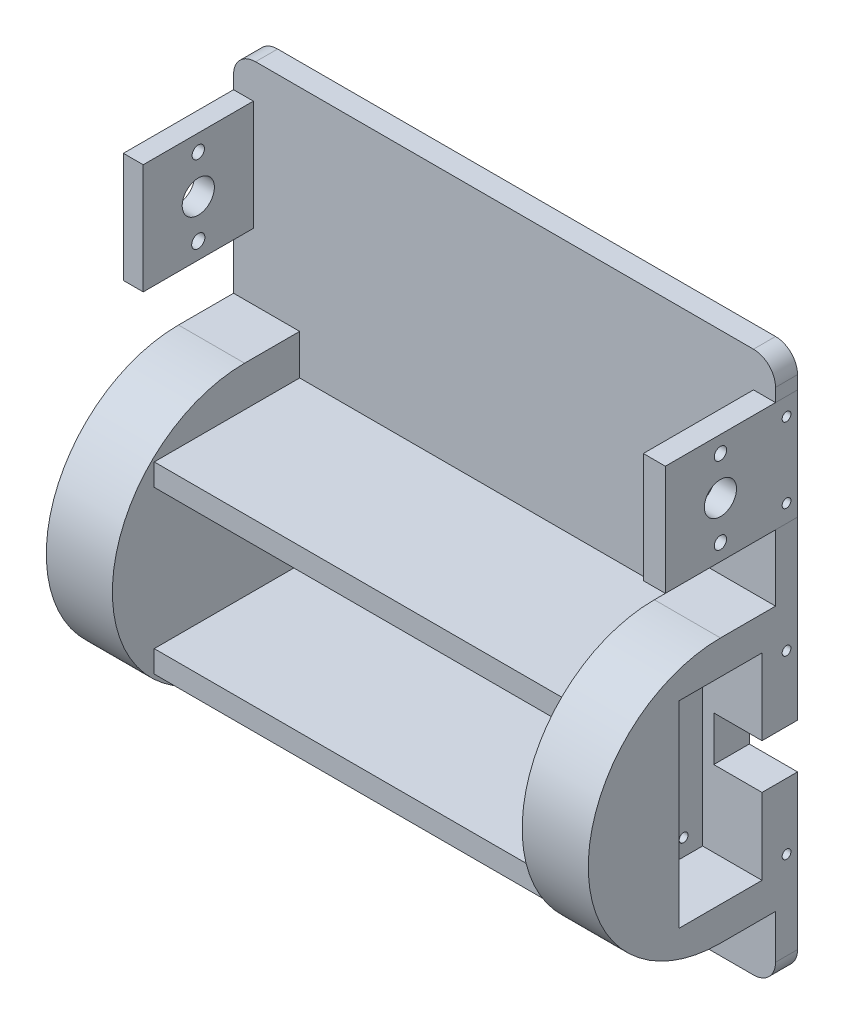
SolidWorks part; units mm, degrees
ref_plane "Plano frontal" through (0, 0, 0) normal (0, 0, 1) x (1, 0, 0)
ref_plane "Plano superior" through (0, 0, 0) normal (0, 1, 0) x (1, 0, 0)
ref_plane "Plano direito" through (0, 0, 0) normal (1, 0, 0) x (0, 0, -1)
sketch "Esboço1" plane through (0, 0, 0) normal (0, 0, 1) x (1, 0, 0)
  line L1 (-47.8109, 58.4855) -> (65.1891, 58.4855)
  line L2 (-52.8109, 53.4855) -> (-52.8109, -59.5145)
  line L3 (-47.8109, -64.5145) -> (65.1891, -64.5145)
  line L4 (70.1891, 53.4855) -> (70.1891, -59.5145)
  arc A0 (70.1891, 53.4855) -> (65.1891, 58.4855) centre (65.1891, 53.4855) ccw
  arc A1 (70.1891, -59.5145) -> (65.1891, -64.5145) centre (65.1891, -59.5145) cw
  arc A2 (-52.8109, -59.5145) -> (-47.8109, -64.5145) centre (-47.8109, -59.5145) ccw
  arc A3 (-52.8109, 53.4855) -> (-47.8109, 58.4855) centre (-47.8109, 53.4855) cw
  dimension "D1" = 5
extrude "Ressalto-extrusão1" add sketch "Esboço1" along normal blind 5
sketch "Esboço4" plane through (0, 0, 5) normal (0, 0, 1) x (1, 0, 0)
  line L0 (-52.8109, 53.4855) -> (-52.8109, -59.5145) construction
  line L1 (-52.8109, 50.4855) -> (-48.3154, 50.4855)
  line L2 (-52.8109, 50.4855) -> (-52.8109, 25.4855)
  line L3 (-52.8109, 25.4855) -> (-48.3154, 25.4855)
  line L4 (-48.3154, 50.4855) -> (-48.3154, 25.4855)
  line L5 (65.1891, 58.4855) -> (-47.8109, 58.4855) construction
  dimension "D1" = 8
extrude "Corte-extrusão2" cut sketch "Esboço4" against normal blind 5
sketch "Esboço5" plane through (0, 0, 5) normal (0, 0, 1) x (1, 0, 0)
  line L1 (-52.8109, 50.4855) -> (-48.3154, 50.4855)
  line L2 (-52.8109, 50.4855) -> (-52.8109, 25.4855)
  line L3 (-52.8109, 25.4855) -> (-48.3154, 25.4855)
  line L4 (-48.3154, 50.4855) -> (-48.3154, 25.4855)
extrude "Ressalto-extrusão2" add sketch "Esboço5" along normal blind 25 and the other way blind 5 separate body
sketch "Esboço6" plane through (-52.8109, 0, 0) normal (-1, 0, 0) x (0, 0, 1)
  line L0 (0, 50.4855) -> (5, 50.4855) construction
  line L1 (0, 50.4855) -> (0, 25.4855) construction
  circle A0 centre (2.5, 46.4855) radius 1
  point P4 (2.5, 50.4855)
  dimension "D1" = 4
  dimension "D2" = 2.5
extrude "Corte-extrusão3" cut sketch "Esboço6" against normal blind 10
sketch "Esboço7" plane through (-52.8109, 0, 0) normal (-1, 0, 0) x (0, 0, 1)
  line L0 (0, 25.4855) -> (5, 25.4855) construction
  line L1 (0, 50.4855) -> (0, 25.4855) construction
  circle A0 centre (2.5, 29.4855) radius 1
  point P4 (2.5, 25.4855)
  dimension "D1" = 4
  dimension "D2" = 2.5
extrude "Corte-extrusão4" cut sketch "Esboço7" against normal blind 10
sketch "Esboço8" plane through (-48.3154, 0, 0) normal (1, 0, 0) x (0, 0, -1)
  line L0 (0, 50.4855) -> (-30, 50.4855) construction
  line L1 (-30, 25.4855) -> (-30, 50.4855) construction
  circle A0 centre (-17.5, 37.9855) radius 3.65
  dimension "D1" = 12.5
  dimension "D2" = 12.5
extrude "Corte-extrusão5" cut sketch "Esboço8" against normal blind 10
sketch "Esboço9" plane through (-52.8109, 0, 0) normal (-1, 0, 0) x (0, 0, 1)
  line L1 (30, 50.4855) -> (30, 25.4855) construction
  circle A0 centre (17.5, 46.7355) radius 1.4
  circle A1 centre (17.5, 37.9855) radius 3.65 construction
  dimension "D1" = 8.75
  dimension "D2" = 12.5
extrude "Corte-extrusão6" cut sketch "Esboço9" against normal blind 10
sketch "Esboço10" plane through (-52.8109, 0, 0) normal (-1, 0, 0) x (0, 0, 1)
  line L0 (30, 50.4855) -> (30, 25.4855) construction
  circle A0 centre (17.5, 29.2355) radius 1.5
  circle A1 centre (17.5, 37.9855) radius 3.65 construction
  dimension "D1" = 8.75
  dimension "D2" = 12.5
extrude "Corte-extrusão7" cut sketch "Esboço10" against normal blind 10
sketch "Esboço11" plane through (0, 0, 5) normal (0, 0, 1) x (1, 0, 0)
  line L0 (70.1891, -59.5145) -> (70.1891, 53.4855) construction
  line L1 (70.1891, 50.4855) -> (65.1891, 50.4855)
  line L2 (70.1891, 50.4855) -> (70.1891, 25.4855)
  line L3 (70.1891, 25.4855) -> (65.1891, 25.4855)
  line L4 (65.1891, 50.4855) -> (65.1891, 25.4855)
  line L5 (65.1891, 58.4855) -> (-47.8109, 58.4855) construction
  dimension "D1" = 8
extrude "Corte-extrusão8" cut sketch "Esboço11" against normal blind 10
sketch "Esboço16" plane through (0, 0, 5) normal (0, 0, 1) x (1, 0, 0)
  line L1 (65.1891, 50.4855) -> (70.1891, 50.4855)
  line L2 (65.1891, 50.4855) -> (65.1891, 25.4855)
  line L3 (65.1891, 25.4855) -> (70.1891, 25.4855)
  line L4 (70.1891, 50.4855) -> (70.1891, 25.4855)
extrude "Ressalto-extrusão3" add sketch "Esboço16" along normal blind 25 and the other way blind 5 separate body
sketch "Esboço17" plane through (70.1891, 0, 0) normal (1, 0, 0) x (0, 0, -1)
  line L0 (0, 50.4855) -> (-5, 50.4855) construction
  line L1 (0, 25.4855) -> (0, 50.4855) construction
  circle A0 centre (-2.5, 46.4855) radius 1
  dimension "D1" = 4
  dimension "D2" = 2.5
extrude "Corte-extrusão9" cut sketch "Esboço17" against normal blind 10
sketch "Esboço18" plane through (70.1891, 0, 0) normal (1, 0, 0) x (0, 0, -1)
  line L0 (0, 25.4855) -> (-30, 25.4855) construction
  line L1 (0, 25.4855) -> (0, 50.4855) construction
  circle A0 centre (-2.5, 29.4855) radius 1
  dimension "D1" = 4
  dimension "D2" = 2.5
extrude "Corte-extrusão10" cut sketch "Esboço18" against normal blind 10
sketch "Esboço20" plane through (70.1891, 0, 0) normal (1, 0, 0) x (0, 0, -1)
  line L0 (-30, 25.4855) -> (-30, 50.4855) construction
  line L1 (0, 50.4855) -> (-30, 50.4855) construction
  circle A0 centre (-17.5, 37.9855) radius 3.65
  dimension "D1" = 12.5
  dimension "D2" = 12.5
extrude "Corte-extrusão11" cut sketch "Esboço20" against normal blind 6
sketch "Esboço22" plane through (70.1891, 0, 0) normal (1, 0, 0) x (0, 0, -1)
  line L1 (-30, 25.4855) -> (-30, 50.4855) construction
  circle A0 centre (-17.5, 46.7355) radius 1.4
  circle A1 centre (-17.5, 37.9855) radius 3.65 construction
  dimension "D1" = 8.75
  dimension "D2" = 12.5
extrude "Corte-extrusão12" cut sketch "Esboço22" against normal blind 5
sketch "Esboço23" plane through (70.1891, 0, 0) normal (1, 0, 0) x (0, 0, -1)
  line L0 (-30, 25.4855) -> (-30, 50.4855) construction
  circle A0 centre (-17.5, 29.2355) radius 1.4
  circle A1 centre (-17.5, 37.9855) radius 3.65 construction
  dimension "D1" = 12.5
  dimension "D2" = 8.75
extrude "Corte-extrusão13" cut sketch "Esboço23" against normal blind 5
sketch "Esboço24" plane through (0, 0, 5) normal (0, 0, 1) x (1, 0, 0)
  line L0 (-52.8109, 25.4855) -> (-52.8109, -59.5145) construction
  line L1 (-52.8109, -49.5145) -> (-37.8109, -49.5145)
  line L2 (-52.8109, -49.5145) -> (-52.8109, 10.4855)
  line L3 (-52.8109, 10.4855) -> (-37.8109, 10.4855)
  line L4 (-37.8109, -49.5145) -> (-37.8109, 10.4855)
  line L6 (-47.8109, -64.5145) -> (65.1891, -64.5145) construction
  dimension "D1" = 15
extrude "Corte-extrusão14" cut sketch "Esboço24" against normal blind 10
sketch "Esboço27" plane through (0, 0, 5) normal (0, 0, 1) x (1, 0, 0)
  line L0 (70.1891, -59.5145) -> (70.1891, 25.4855) construction
  line L1 (70.1891, -49.5145) -> (55.1891, -49.5145)
  line L2 (70.1891, -49.5145) -> (70.1891, 10.4855)
  line L3 (70.1891, 10.4855) -> (55.1891, 10.4855)
  line L4 (55.1891, -49.5145) -> (55.1891, 10.4855)
  line L5 (-52.8109, -49.5145) -> (-37.8109, -49.5145) construction
  line L6 (-47.8109, -64.5145) -> (65.1891, -64.5145) construction
  dimension "D1" = 15
  dimension "D2" = 15
extrude "Corte-extrusão16" cut sketch "Esboço27" against normal blind 25
sketch "Esboço32" plane through (0, 0, 5) normal (0, 0, 1) x (1, 0, 0)
  line L0 (0, -19.25) -> (0, 19.25) construction
  line L1 (-52.8109, 10.4855) -> (-37.8109, 10.4855)
  line L2 (-52.8109, 10.4855) -> (-52.8109, -49.5145)
  line L3 (-52.8109, -49.5145) -> (-37.8109, -49.5145)
  line L4 (-37.8109, 10.4855) -> (-37.8109, -49.5145)
extrude "Ressalto-extrusão7" add sketch "Esboço32" along normal blind 12.5 and the other way blind 5 separate body
sketch "Esboço33" plane through (-52.8109, 0, 0) normal (-1, 0, 0) x (0, 0, 1)
  line L4 (0, -49.5145) -> (17.5, -49.5145)
  line L5 (17.5, -49.5145) -> (17.5, 10.4855)
  line L6 (17.5, 10.4855) -> (0, 10.4855)
  line L7 (0, 10.4855) -> (0, -49.5145)
  line L8 (0, -49.5145) -> (17.5, -49.5145)
  line L10 (17.5, 10.4855) -> (0, 10.4855)
  line L11 (0, 10.4855) -> (0, -49.5145)
  arc A0 (17.5, 10.4855) -> (17.5, -49.5145) centre (17.5, -19.5145) cw
  dimension "D1" = 0
extrude "Ressalto-extrusão8" add sketch "Esboço33" against normal blind 15 separate body
sketch "Esboço34" plane through (0, 0, 5) normal (0, 0, 1) x (1, 0, 0)
  line L1 (55.1891, 10.4855) -> (70.1891, 10.4855)
  line L2 (55.1891, 10.4855) -> (55.1891, -49.5145)
  line L3 (55.1891, -49.5145) -> (70.1891, -49.5145)
  line L4 (70.1891, 10.4855) -> (70.1891, -49.5145)
extrude "Ressalto-extrusão9" add sketch "Esboço34" along normal blind 12.5 and the other way blind 5 separate body
sketch "Esboço35" plane through (70.1891, 0, 0) normal (1, 0, 0) x (0, 0, -1)
  line L4 (0, 10.4855) -> (-17.5, 10.4855)
  line L5 (-17.5, 10.4855) -> (-17.5, -49.5145)
  line L6 (-17.5, -49.5145) -> (0, -49.5145)
  line L7 (0, -49.5145) -> (0, 10.4855)
  line L8 (0, 10.4855) -> (-17.5, 10.4855)
  line L10 (-17.5, -49.5145) -> (0, -49.5145)
  line L11 (0, -49.5145) -> (0, 10.4855)
  arc A0 (-17.5, -49.5145) -> (-17.5, 10.4855) centre (-17.5, -19.5145) cw
  dimension "D1" = 0
extrude "Ressalto-extrusão10" add sketch "Esboço35" against normal blind 15 separate body
sketch "Esboço36" plane through (70.1891, 0, 0) normal (1, 0, 0) x (0, 0, -1)
  line L0 (-17.5, -49.5145) -> (0, -49.5145) construction
  line L1 (0, -49.5145) -> (0, 10.4855) construction
  circle A0 centre (-2.5, -39.5145) radius 1
  circle A2 centre (-2.5, 0.4855) radius 1
  dimension "D1" = 10
  dimension "D2" = 2.5
  dimension "D5" = 2.5
  dimension "D6" = 50
extrude "Corte-extrusão18" cut sketch "Esboço36" against normal blind 20
sketch "Esboço37" plane through (-52.8109, 0, 0) normal (-1, 0, 0) x (0, 0, 1)
  line L0 (0, 10.4855) -> (5, 10.4855) construction
  line L1 (0, 10.4855) -> (0, -49.5145) construction
  circle A0 centre (2.5, 0.4855) radius 1
  circle A2 centre (2.5, -39.5145) radius 1
  dimension "D1" = 10
  dimension "D2" = 2.5
  dimension "D5" = 50
  dimension "D6" = 2.5
extrude "Corte-extrusão19" cut sketch "Esboço37" against normal blind 20
sketch "Esboço39" plane through (70.1891, 0, 0) normal (1, 0, 0) x (0, 0, -1)
  line L1 (-26.9163, -41.876) -> (-8.0663, -41.876)
  line L2 (-26.9163, -41.876) -> (-26.9163, 2.829)
  line L3 (-26.9163, 2.829) -> (-8.0663, 2.829)
  line L4 (-8.0663, -41.876) -> (-8.0663, 2.829)
extrude "Corte-extrusão20" cut sketch "Esboço39" against normal blind 13.49
sketch "Esboço41" plane through (56.6991, 0, 0) normal (1, 0, 0) x (0, 0, -1)
  line L0 (-8.0663, 2.829) -> (-26.9163, 2.829) construction
  line L1 (-26.9163, 2.829) -> (-26.9163, -41.876) construction
  circle A0 centre (-20.3753, -0.981) radius 1.6255
  circle A1 centre (-12.3753, -0.981) radius 1
  dimension "D1" = 3.81
  dimension "D2" = 6.541
  dimension "D3" = 8
sketch "Esboço42" plane through (56.6991, 0, 0) normal (1, 0, 0) x (0, 0, -1)
  line L0 (-26.9163, 2.829) -> (-26.9163, -41.876) construction
  line L1 (-26.9163, -41.876) -> (-8.0663, -41.876) construction
  circle A0 centre (-20.3753, -38.066) radius 1.6255
  circle A1 centre (-12.3753, -38.066) radius 1
  dimension "D1" = 6.541
  dimension "D3" = 8
  dimension "D2" = 3.81
sketch "Esboço43" plane through (0, 0, 8.0663) normal (0, 0, 1) x (1, 0, 0)
  line L1 (59.2391, -24.5945) -> (70.1891, -24.5945)
  line L2 (59.2391, -24.5945) -> (59.2391, -14.4345)
  line L3 (59.2391, -14.4345) -> (70.1891, -14.4345)
  line L4 (70.1891, -24.5945) -> (70.1891, -14.4345)
  line L6 (56.6991, -41.876) -> (56.6991, 2.829) construction
  line L7 (55.1891, -49.5145) -> (70.1891, -49.5145) construction
  line L8 (70.1891, 10.4855) -> (55.1891, 10.4855) construction
  line L9 (70.1891, -41.876) -> (70.1891, 2.829) construction
  point P8 (64.7141, -14.4345)
  dimension "D1" = 2.54
  dimension "D2" = 24.92
  dimension "D3" = 24.92
extrude "Corte-extrusão23" cut sketch "Esboço43" against normal blind 10
sketch "Esboço44" plane through (55.1891, 0, 0) normal (-1, 0, 0) x (0, 0, 1)
  line L0 (5, 10.4855) -> (5, -49.5145) construction
  line L1 (38, 1.3305) -> (5, 1.3305)
  line L2 (38, 1.3305) -> (38, -3.6695)
  line L3 (38, -3.6695) -> (5, -3.6695)
  line L4 (5, 1.3305) -> (5, -3.6695)
extrude "Ressalto-extrusão11" add sketch "Esboço44" along normal blind 93 separate body
sketch "Esboço47" plane through (55.1891, 0, 0) normal (-1, 0, 0) x (0, 0, 1)
  line L0 (5, 10.4855) -> (5, -49.5145) construction
  line L1 (5, -35.3645) -> (38, -35.3645)
  line L2 (5, -35.3645) -> (5, -40.3645)
  line L3 (5, -40.3645) -> (38, -40.3645)
  line L4 (38, -35.3645) -> (38, -40.3645)
  line L5 (38, 1.3305) -> (5, 1.3305) construction
  line L6 (0, 10.4855) -> (17.5, 10.4855) construction
  line L7 (17.5, -49.5145) -> (0, -49.5145) construction
  dimension "D1" = 9.155
  dimension "D2" = 9.15
extrude "Ressalto-extrusão12" add sketch "Esboço47" along normal blind 93
extrude "Corte-extrusão25" cut sketch "Esboço41" against normal blind 31
extrude "Corte-extrusão26" cut sketch "Esboço42" against normal blind 31
sketch "Esboço52" plane through (-52.8109, 0, 0) normal (-1, 0, 0) x (0, 0, 1)
  line L1 (29.6732, 2.8455) -> (10.8232, 2.8455)
  line L2 (29.6732, 2.8455) -> (29.6732, -41.8595)
  line L3 (29.6732, -41.8595) -> (10.8232, -41.8595)
  line L4 (10.8232, 2.8455) -> (10.8232, -41.8595)
  line L7 (5, 10.4855) -> (17.5, 10.4855) construction
  point P15 (11.25, 10.4855)
  dimension "D2" = 7.64
extrude "Corte-extrusão27" cut sketch "Esboço52" against normal blind 13.49
sketch "Esboço54" plane through (0, 0, 10.8232) normal (0, 0, 1) x (1, 0, 0)
  line L0 (-52.8109, 2.8455) -> (-52.8109, -41.8595) construction
  line L1 (-52.8109, -14.4345) -> (-41.8599, -14.4345)
  line L2 (-52.8109, -14.4345) -> (-52.8109, -24.5945)
  line L3 (-52.8109, -24.5945) -> (-41.8599, -24.5945)
  line L4 (-41.8599, -14.4345) -> (-41.8599, -24.5945)
  line L5 (-52.8109, -49.5145) -> (-37.8109, -49.5145) construction
  line L6 (-37.8109, 10.4855) -> (-52.8109, 10.4855) construction
  dimension "D1" = 24.92
  dimension "D2" = 24.92
extrude "Corte-extrusão28" cut sketch "Esboço54" against normal blind 24
sketch "Esboço55" plane through (-39.3209, 0, 0) normal (-1, 0, 0) x (0, 0, 1)
  line L0 (29.6732, -41.8595) -> (29.6732, 2.8455) construction
  line L1 (29.6732, 2.8455) -> (10.8232, 2.8455) construction
  line L2 (10.8232, -41.8595) -> (29.6732, -41.8595) construction
  line L3 (29.6732, -41.8595) -> (29.6732, 2.8455) construction
  circle A0 centre (23.1332, -0.9645) radius 1.6255
  circle A1 centre (23.1332, -38.0495) radius 1.6255
  circle A2 centre (15.1332, -0.9645) radius 1
  circle A3 centre (15.1332, -38.0495) radius 1
  dimension "D1" = 6.54
  dimension "D3" = 3.81
  dimension "D5" = 8
  dimension "D2" = 3.81
  dimension "D4" = 6.54
extrude "Corte-extrusão29" cut sketch "Esboço55" against normal blind 31
